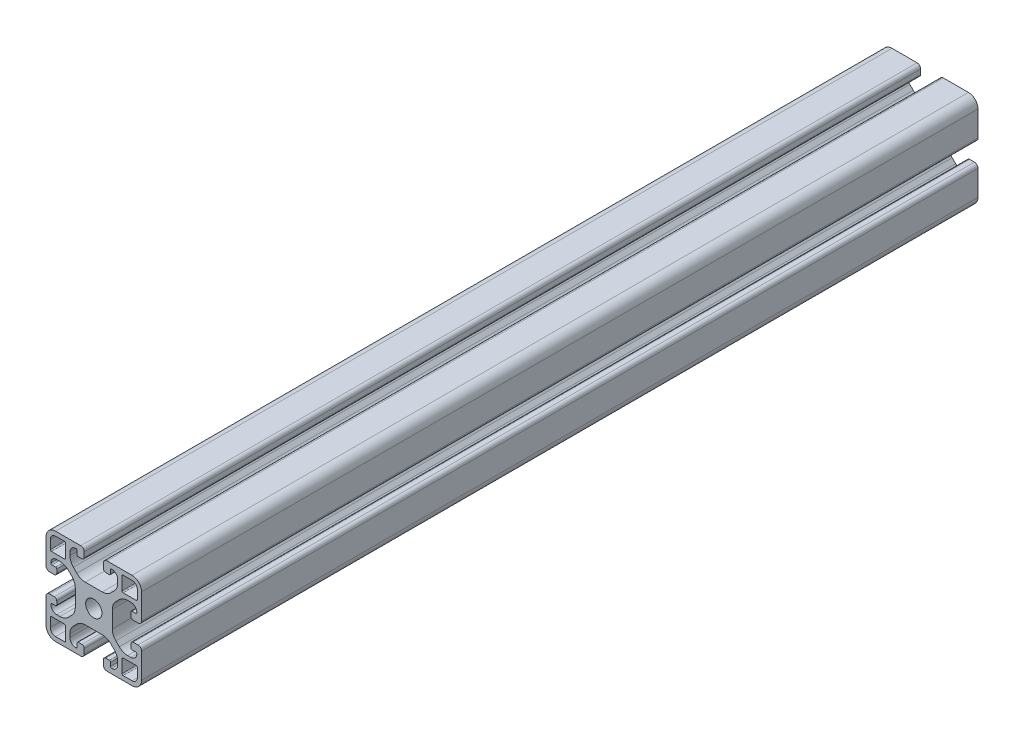
SolidWorks part; units mm, degrees
ref_plane "Plan de face" through (0, 0, 0) normal (0, 0, 1) x (1, 0, 0)
ref_plane "Plan de dessus" through (0, 0, 0) normal (0, 1, 0) x (1, 0, 0)
ref_plane "Plan de droite" through (0, 0, 0) normal (1, 0, 0) x (0, 0, -1)
ref_plane "Plan1" through (0, 0, -30) normal (0, 0, -1) x (-1, 0, 0)
sketch "Esquisse1" plane through (0, 0, -30) normal (0, 0, -1) x (-1, 0, 0)
  line B0 (-4.5, 15) -> (-4.5, 13.5)
  line B1 (-4, 13) -> (-2.5, 13)
  line B2 (-4.5, 10) -> (-5.8076, 10)
  line B3 (-9.3431, 11.4645) -> (-10.7855, 12.9069)
  line B4 (-12.25, 16.4424) -> (-12.25, 23.5576)
  line B5 (-10.7855, 27.0931) -> (-9.3431, 28.5355)
  line B6 (-5.8076, 30) -> (-4.5, 30)
  line B7 (-2.5, 27) -> (-4, 27)
  line B8 (-4.5, 26.5) -> (-4.5, 25)
  line B9 (-3.5, 24) -> (-1.5, 24)
  line B10 (0, 25.5) -> (0, 36)
  line B11 (-4, 40) -> (-14.5, 40)
  line B12 (-16, 38.5) -> (-16, 36.5)
  line B13 (-15, 35.5) -> (-13.5, 35.5)
  line B14 (-13, 36) -> (-13, 37.5)
  line B15 (-10, 35.5) -> (-10, 34.1924)
  line B16 (-11.4645, 30.6569) -> (-12.9069, 29.2145)
  line B17 (-16.4424, 27.75) -> (-23.5576, 27.75)
  line B18 (-27.0931, 29.2145) -> (-28.5355, 30.6569)
  line B19 (-30, 34.1924) -> (-30, 35.5)
  line B20 (-27, 37.5) -> (-27, 36)
  line B21 (-26.5, 35.5) -> (-25, 35.5)
  line B22 (-24, 36.5) -> (-24, 38.5)
  line B23 (-25.5, 40) -> (-36, 40)
  line B24 (-40, 36) -> (-40, 25.5)
  line B25 (-38.5, 24) -> (-36.5, 24)
  line B26 (-35.5, 25) -> (-35.5, 26.5)
  line B27 (-36, 27) -> (-37.5, 27)
  line B28 (-35.5, 30) -> (-34.1924, 30)
  line B29 (-30.6569, 28.5355) -> (-29.2145, 27.0931)
  line B30 (-27.75, 23.5576) -> (-27.75, 16.4424)
  line B31 (-29.2145, 12.9069) -> (-30.6569, 11.4645)
  line B32 (-34.1924, 10) -> (-35.5, 10)
  line B33 (-37.5, 13) -> (-36, 13)
  line B34 (-35.5, 13.5) -> (-35.5, 15)
  line B35 (-36.5, 16) -> (-38.5, 16)
  line B36 (-40, 14.5) -> (-40, 4)
  line B37 (-36, 0) -> (-25.5, 0)
  line B38 (-24, 1.5) -> (-24, 3.5)
  line B39 (-25, 4.5) -> (-26.5, 4.5)
  line B40 (-27, 4) -> (-27, 2.5)
  line B41 (-30, 4.5) -> (-30, 5.8076)
  line B42 (-28.5355, 9.3431) -> (-27.0931, 10.7855)
  line B43 (-23.5576, 12.25) -> (-16.4424, 12.25)
  line B44 (-12.9069, 10.7855) -> (-11.4645, 9.3431)
  line B45 (-10, 5.8076) -> (-10, 4.5)
  line B46 (-13, 2.5) -> (-13, 4)
  line B47 (-13.5, 4.5) -> (-15, 4.5)
  line B48 (-16, 3.5) -> (-16, 1.5)
  line B49 (-14.5, 0) -> (-4, 0)
  line B50 (0, 4) -> (0, 14.5)
  line B51 (-1.5, 16) -> (-3.5, 16)
  line B52 (-4, 1.8) -> (-7.7, 1.8)
  line B53 (-8.2, 2.3) -> (-8.2, 7.7)
  line B54 (-7.7, 8.2) -> (-2.3, 8.2)
  line B55 (-1.8, 7.7) -> (-1.8, 4)
  line B56 (-38.2, 4) -> (-38.2, 7.7)
  line B57 (-37.7, 8.2) -> (-32.3, 8.2)
  line B58 (-31.8, 7.7) -> (-31.8, 2.3)
  line B59 (-32.3, 1.8) -> (-36, 1.8)
  line B60 (-36, 38.2) -> (-32.3, 38.2)
  line B61 (-31.8, 37.7) -> (-31.8, 32.3)
  line B62 (-32.3, 31.8) -> (-37.7, 31.8)
  line B63 (-38.2, 32.3) -> (-38.2, 36)
  line B64 (-1.8, 36) -> (-1.8, 32.3)
  line B65 (-2.3, 31.8) -> (-7.7, 31.8)
  line B66 (-8.2, 32.3) -> (-8.2, 37.7)
  line B67 (-7.7, 38.2) -> (-4, 38.2)
  arc B68 (-4.5, 13.5) -> (-4, 13) centre (-4, 13.5) ccw
  arc B69 (-2.5, 13) -> (-2, 12.5) centre (-2.5, 12.5) cw
  arc B70 (-2, 12.5) -> (-4.5, 10) centre (-4.5, 12.5) cw
  arc B71 (-5.8076, 10) -> (-9.3431, 11.4645) centre (-5.8076, 15) cw
  arc B72 (-10.7855, 12.9069) -> (-12.25, 16.4424) centre (-7.25, 16.4424) cw
  arc B73 (-12.25, 23.5576) -> (-10.7855, 27.0931) centre (-7.25, 23.5576) cw
  arc B74 (-9.3431, 28.5355) -> (-5.8076, 30) centre (-5.8076, 25) cw
  arc B75 (-4.5, 30) -> (-2, 27.5) centre (-4.5, 27.5) cw
  arc B76 (-2, 27.5) -> (-2.5, 27) centre (-2.5, 27.5) cw
  arc B77 (-4, 27) -> (-4.5, 26.5) centre (-4, 26.5) ccw
  arc B78 (-4.5, 25) -> (-3.5, 24) centre (-3.5, 25) ccw
  arc B79 (-1.5, 24) -> (0, 25.5) centre (-1.5, 25.5) ccw
  arc B80 (0, 36) -> (-4, 40) centre (-4, 36) ccw
  arc B81 (-14.5, 40) -> (-16, 38.5) centre (-14.5, 38.5) ccw
  arc B82 (-16, 36.5) -> (-15, 35.5) centre (-15, 36.5) ccw
  arc B83 (-13.5, 35.5) -> (-13, 36) centre (-13.5, 36) ccw
  arc B84 (-13, 37.5) -> (-12.5, 38) centre (-12.5, 37.5) cw
  arc B85 (-12.5, 38) -> (-10, 35.5) centre (-12.5, 35.5) cw
  arc B86 (-10, 34.1924) -> (-11.4645, 30.6569) centre (-15, 34.1924) cw
  arc B87 (-12.9069, 29.2145) -> (-16.4424, 27.75) centre (-16.4424, 32.75) cw
  arc B88 (-23.5576, 27.75) -> (-27.0931, 29.2145) centre (-23.5576, 32.75) cw
  arc B89 (-28.5355, 30.6569) -> (-30, 34.1924) centre (-25, 34.1924) cw
  arc B90 (-30, 35.5) -> (-27.5, 38) centre (-27.5, 35.5) cw
  arc B91 (-27.5, 38) -> (-27, 37.5) centre (-27.5, 37.5) cw
  arc B92 (-27, 36) -> (-26.5, 35.5) centre (-26.5, 36) ccw
  arc B93 (-25, 35.5) -> (-24, 36.5) centre (-25, 36.5) ccw
  arc B94 (-24, 38.5) -> (-25.5, 40) centre (-25.5, 38.5) ccw
  arc B95 (-36, 40) -> (-40, 36) centre (-36, 36) ccw
  arc B96 (-40, 25.5) -> (-38.5, 24) centre (-38.5, 25.5) ccw
  arc B97 (-36.5, 24) -> (-35.5, 25) centre (-36.5, 25) ccw
  arc B98 (-35.5, 26.5) -> (-36, 27) centre (-36, 26.5) ccw
  arc B99 (-37.5, 27) -> (-38, 27.5) centre (-37.5, 27.5) cw
  arc B100 (-38, 27.5) -> (-35.5, 30) centre (-35.5, 27.5) cw
  arc B101 (-34.1924, 30) -> (-30.6569, 28.5355) centre (-34.1924, 25) cw
  arc B102 (-29.2145, 27.0931) -> (-27.75, 23.5576) centre (-32.75, 23.5576) cw
  arc B103 (-27.75, 16.4424) -> (-29.2145, 12.9069) centre (-32.75, 16.4424) cw
  arc B104 (-30.6569, 11.4645) -> (-34.1924, 10) centre (-34.1924, 15) cw
  arc B105 (-35.5, 10) -> (-38, 12.5) centre (-35.5, 12.5) cw
  arc B106 (-38, 12.5) -> (-37.5, 13) centre (-37.5, 12.5) cw
  arc B107 (-36, 13) -> (-35.5, 13.5) centre (-36, 13.5) ccw
  arc B108 (-35.5, 15) -> (-36.5, 16) centre (-36.5, 15) ccw
  arc B109 (-38.5, 16) -> (-40, 14.5) centre (-38.5, 14.5) ccw
  arc B110 (-40, 4) -> (-36, 0) centre (-36, 4) ccw
  arc B111 (-25.5, 0) -> (-24, 1.5) centre (-25.5, 1.5) ccw
  arc B112 (-24, 3.5) -> (-25, 4.5) centre (-25, 3.5) ccw
  arc B113 (-26.5, 4.5) -> (-27, 4) centre (-26.5, 4) ccw
  arc B114 (-27, 2.5) -> (-27.5, 2) centre (-27.5, 2.5) cw
  arc B115 (-27.5, 2) -> (-30, 4.5) centre (-27.5, 4.5) cw
  arc B116 (-30, 5.8076) -> (-28.5355, 9.3431) centre (-25, 5.8076) cw
  arc B117 (-27.0931, 10.7855) -> (-23.5576, 12.25) centre (-23.5576, 7.25) cw
  arc B118 (-16.4424, 12.25) -> (-12.9069, 10.7855) centre (-16.4424, 7.25) cw
  arc B119 (-11.4645, 9.3431) -> (-10, 5.8076) centre (-15, 5.8076) cw
  arc B120 (-10, 4.5) -> (-12.5, 2) centre (-12.5, 4.5) cw
  arc B121 (-12.5, 2) -> (-13, 2.5) centre (-12.5, 2.5) cw
  arc B122 (-13, 4) -> (-13.5, 4.5) centre (-13.5, 4) ccw
  arc B123 (-15, 4.5) -> (-16, 3.5) centre (-15, 3.5) ccw
  arc B124 (-16, 1.5) -> (-14.5, 0) centre (-14.5, 1.5) ccw
  arc B125 (-4, 0) -> (0, 4) centre (-4, 4) ccw
  arc B126 (0, 14.5) -> (-1.5, 16) centre (-1.5, 14.5) ccw
  arc B127 (-3.5, 16) -> (-4.5, 15) centre (-3.5, 15) ccw
  circle B128 centre (-20, 20) radius 3.4
  arc B129 (-1.8, 4) -> (-4, 1.8) centre (-4, 4) cw
  arc B130 (-7.7, 1.8) -> (-8.2, 2.3) centre (-7.7, 2.3) cw
  arc B131 (-8.2, 7.7) -> (-7.7, 8.2) centre (-7.7, 7.7) cw
  arc B132 (-2.3, 8.2) -> (-1.8, 7.7) centre (-2.3, 7.7) cw
  arc B133 (-36, 1.8) -> (-38.2, 4) centre (-36, 4) cw
  arc B134 (-38.2, 7.7) -> (-37.7, 8.2) centre (-37.7, 7.7) cw
  arc B135 (-32.3, 8.2) -> (-31.8, 7.7) centre (-32.3, 7.7) cw
  arc B136 (-31.8, 2.3) -> (-32.3, 1.8) centre (-32.3, 2.3) cw
  arc B137 (-38.2, 36) -> (-36, 38.2) centre (-36, 36) cw
  arc B138 (-32.3, 38.2) -> (-31.8, 37.7) centre (-32.3, 37.7) cw
  arc B139 (-31.8, 32.3) -> (-32.3, 31.8) centre (-32.3, 32.3) cw
  arc B140 (-37.7, 31.8) -> (-38.2, 32.3) centre (-37.7, 32.3) cw
  arc B141 (-4, 38.2) -> (-1.8, 36) centre (-4, 36) cw
  arc B142 (-1.8, 32.3) -> (-2.3, 31.8) centre (-2.3, 32.3) cw
  arc B143 (-7.7, 31.8) -> (-8.2, 32.3) centre (-7.7, 32.3) cw
  arc B144 (-8.2, 37.7) -> (-7.7, 38.2) centre (-7.7, 37.7) cw
sketch_block_instance "Bloc1-1"
sketch_block "Bloc1"
extrude "Boss.-Extru.1" add sketch "Esquisse1" against normal blind 350
